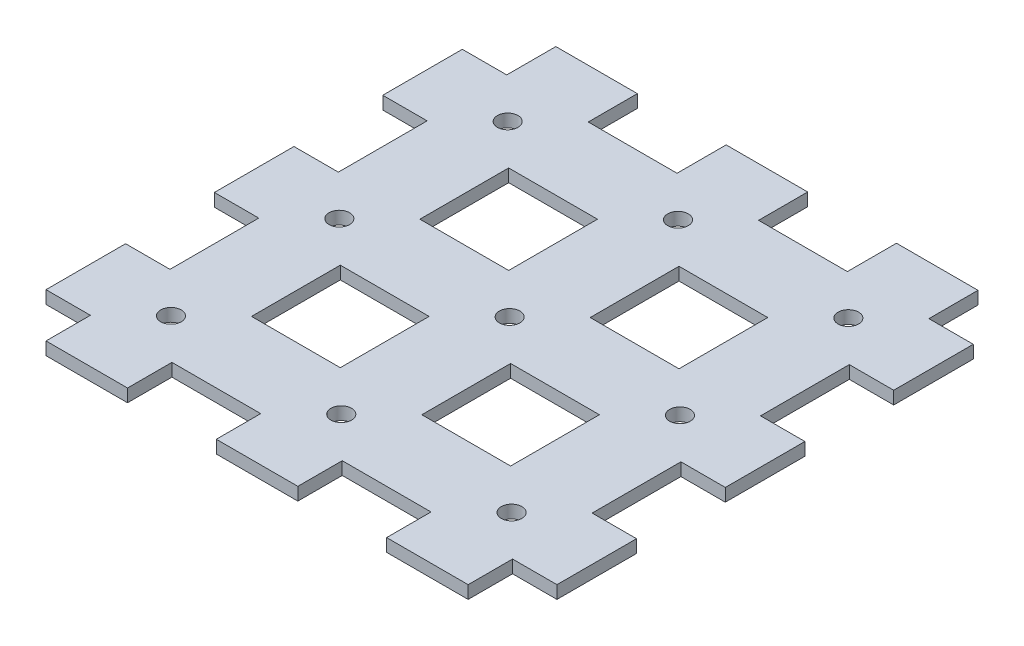
SolidWorks part; units mm, degrees
ref_plane "Front Plane" through (0, 0, 0) normal (0, 0, 1) x (1, 0, 0)
ref_plane "Top Plane" through (0, 0, 0) normal (0, 1, 0) x (1, 0, 0)
ref_plane "Right Plane" through (0, 0, 0) normal (1, 0, 0) x (0, 0, -1)
sketch "Sketch2" plane through (0, 0, 0) normal (0, 1, 0) x (1, 0, 0)
  line L1 (-63.3, 63.165) -> (63.3, 63.165)
  line L2 (-63.3, 63.165) -> (-63.3, -63.165)
  line L3 (-63.3, -63.165) -> (63.3, -63.165)
  line L4 (63.3, 63.165) -> (63.3, -63.165)
  line L5 (-63.3, 63.165) -> (63.3, -63.165) construction
  line L6 (-63.3, -63.165) -> (63.3, 63.165) construction
  point P0 (0, 0)
  dimension "D1" = 126.6
  dimension "D2" = 126.33
extrude "Boss-Extrude1" add sketch "Sketch2" along normal blind 3.175
sketch "Sketch3" plane through (0, 3.175, 0) normal (0, 1, 0) x (1, 0, 0)
  line L0 (63.3, -63.165) -> (63.3, 63.165) construction
  line L1 (52.3, -52.165) -> (74.3, -52.165)
  line L2 (52.3, -52.165) -> (52.3, -74.165)
  line L3 (52.3, -74.165) -> (74.3, -74.165)
  line L4 (74.3, -52.165) -> (74.3, -74.165)
  line L5 (52.3, -52.165) -> (74.3, -74.165) construction
  line L6 (52.3, -74.165) -> (74.3, -52.165) construction
  line L7 (-63.3, -63.165) -> (63.3, -63.165) construction
  line L8 (10.1, -52.165) -> (32.1, -52.165)
  line L9 (10.1, -52.165) -> (10.1, -74.165)
  line L10 (10.1, -74.165) -> (32.1, -74.165)
  line L11 (32.1, -52.165) -> (32.1, -74.165)
  line L12 (10.1, -52.165) -> (32.1, -74.165) construction
  line L13 (10.1, -74.165) -> (32.1, -52.165) construction
  line L14 (-32.1, -52.165) -> (-10.1, -52.165)
  line L15 (-32.1, -52.165) -> (-32.1, -74.165)
  line L16 (-32.1, -74.165) -> (-10.1, -74.165)
  line L17 (-10.1, -52.165) -> (-10.1, -74.165)
  line L18 (-32.1, -52.165) -> (-10.1, -74.165) construction
  line L19 (-32.1, -74.165) -> (-10.1, -52.165) construction
  line L20 (-74.3, -52.165) -> (-52.3, -52.165)
  line L21 (-74.3, -52.165) -> (-74.3, -74.165)
  line L22 (-74.3, -74.165) -> (-52.3, -74.165)
  line L23 (-52.3, -52.165) -> (-52.3, -74.165)
  line L24 (-74.3, -52.165) -> (-52.3, -74.165) construction
  line L25 (-74.3, -74.165) -> (-52.3, -52.165) construction
  line L26 (10.1, -10.445) -> (32.1, -10.445)
  line L27 (10.1, -10.445) -> (10.1, -32.445)
  line L28 (10.1, -32.445) -> (32.1, -32.445)
  line L29 (32.1, -10.445) -> (32.1, -32.445)
  line L30 (10.1, -10.445) -> (32.1, -32.445) construction
  line L31 (10.1, -32.445) -> (32.1, -10.445) construction
  line L32 (-32.1, -10.445) -> (-10.1, -10.445)
  line L33 (-32.1, -10.445) -> (-32.1, -32.445)
  line L34 (-32.1, -32.445) -> (-10.1, -32.445)
  line L35 (-10.1, -10.445) -> (-10.1, -32.445)
  line L36 (-32.1, -10.445) -> (-10.1, -32.445) construction
  line L37 (-32.1, -32.445) -> (-10.1, -10.445) construction
  line L38 (-74.3, -10.445) -> (-52.3, -10.445)
  line L39 (-74.3, -10.445) -> (-74.3, -32.445)
  line L40 (-74.3, -32.445) -> (-52.3, -32.445)
  line L41 (-52.3, -10.445) -> (-52.3, -32.445)
  line L42 (-74.3, -10.445) -> (-52.3, -32.445) construction
  line L43 (-74.3, -32.445) -> (-52.3, -10.445) construction
  line L44 (10.1, 31.275) -> (32.1, 31.275)
  line L45 (10.1, 31.275) -> (10.1, 9.275)
  line L46 (10.1, 9.275) -> (32.1, 9.275)
  line L47 (32.1, 31.275) -> (32.1, 9.275)
  line L48 (10.1, 31.275) -> (32.1, 9.275) construction
  line L49 (10.1, 9.275) -> (32.1, 31.275) construction
  line L50 (-32.1, 31.275) -> (-10.1, 31.275)
  line L51 (-32.1, 31.275) -> (-32.1, 9.275)
  line L52 (-32.1, 9.275) -> (-10.1, 9.275)
  line L53 (-10.1, 31.275) -> (-10.1, 9.275)
  line L54 (-32.1, 31.275) -> (-10.1, 9.275) construction
  line L55 (-32.1, 9.275) -> (-10.1, 31.275) construction
  line L56 (-74.3, 31.275) -> (-52.3, 31.275)
  line L57 (-74.3, 31.275) -> (-74.3, 9.275)
  line L58 (-74.3, 9.275) -> (-52.3, 9.275)
  line L59 (-52.3, 31.275) -> (-52.3, 9.275)
  line L60 (-74.3, 31.275) -> (-52.3, 9.275) construction
  line L61 (-74.3, 9.275) -> (-52.3, 31.275) construction
  line L62 (10.1, 72.995) -> (32.1, 72.995)
  line L63 (10.1, 72.995) -> (10.1, 50.995)
  line L64 (10.1, 50.995) -> (32.1, 50.995)
  line L65 (32.1, 72.995) -> (32.1, 50.995)
  line L66 (10.1, 72.995) -> (32.1, 50.995) construction
  line L67 (10.1, 50.995) -> (32.1, 72.995) construction
  line L68 (-32.1, 72.995) -> (-10.1, 72.995)
  line L69 (-32.1, 72.995) -> (-32.1, 50.995)
  line L70 (-32.1, 50.995) -> (-10.1, 50.995)
  line L71 (-10.1, 72.995) -> (-10.1, 50.995)
  line L72 (-32.1, 72.995) -> (-10.1, 50.995) construction
  line L73 (-32.1, 50.995) -> (-10.1, 72.995) construction
  line L74 (-74.3, 72.995) -> (-52.3, 72.995)
  line L75 (-74.3, 72.995) -> (-74.3, 50.995)
  line L76 (-74.3, 50.995) -> (-52.3, 50.995)
  line L77 (-52.3, 72.995) -> (-52.3, 50.995)
  line L78 (-74.3, 72.995) -> (-52.3, 50.995) construction
  line L79 (-74.3, 50.995) -> (-52.3, 72.995) construction
  line L80 (52.3, -10.445) -> (74.3, -10.445)
  line L81 (52.3, -10.445) -> (52.3, -32.445)
  line L82 (52.3, -32.445) -> (74.3, -32.445)
  line L83 (74.3, -10.445) -> (74.3, -32.445)
  line L84 (52.3, -10.445) -> (74.3, -32.445) construction
  line L85 (52.3, -32.445) -> (74.3, -10.445) construction
  line L86 (52.3, 31.275) -> (74.3, 31.275)
  line L87 (52.3, 31.275) -> (52.3, 9.275)
  line L88 (52.3, 9.275) -> (74.3, 9.275)
  line L89 (74.3, 31.275) -> (74.3, 9.275)
  line L90 (52.3, 31.275) -> (74.3, 9.275) construction
  line L91 (52.3, 9.275) -> (74.3, 31.275) construction
  line L92 (52.3, 72.995) -> (74.3, 72.995)
  line L93 (52.3, 72.995) -> (52.3, 50.995)
  line L94 (52.3, 50.995) -> (74.3, 50.995)
  line L95 (74.3, 72.995) -> (74.3, 50.995)
  line L96 (52.3, 72.995) -> (74.3, 50.995) construction
  line L97 (52.3, 50.995) -> (74.3, 72.995) construction
  point P0 (63.3, -63.165)
  point P12 (21.1, -63.165)
  point P17 (-21.1, -63.165)
  point P22 (-63.3, -63.165)
  point P27 (21.1, -21.445)
  point P32 (-21.1, -21.445)
  point P37 (-63.3, -21.445)
  point P42 (21.1, 20.275)
  point P47 (-21.1, 20.275)
  point P52 (-63.3, 20.275)
  point P57 (21.1, 61.995)
  point P62 (-21.1, 61.995)
  point P67 (-63.3, 61.995)
  point P72 (63.3, -21.445)
  point P77 (63.3, 20.275)
  point P82 (63.3, 61.995)
  dimension "D1" = 0
  dimension "D2" = 0
  dimension "D3" = 22
  dimension "D4" = 22
  dimension "D7" = 42.2
  dimension "D8" = 41.72
  dimension "D5" = 4
  dimension "D6" = 4
extrude "Cut-Extrude1" cut sketch "Sketch3" against normal through all
sketch "Sketch4" plane through (0, 3.175, 0) normal (0, 1, 0) x (1, 0, 0)
  line L0 (21.1, -32.445) -> (21.1, -52.165) construction
  line L1 (10.1, -32.445) -> (32.1, -32.445) construction
  line L2 (32.1, -52.165) -> (10.1, -52.165) construction
  line L3 (32.1, -57.665) -> (52.3, -57.665) construction
  line L4 (32.1, -63.165) -> (32.1, -52.165) construction
  line L5 (52.3, -52.165) -> (52.3, -63.165) construction
  circle A0 centre (42.2, -42.305) radius 2.55
  circle A1 centre (0, -42.305) radius 2.55
  circle A2 centre (-42.2, -42.305) radius 2.55
  circle A3 centre (0, -0.585) radius 2.55
  circle A4 centre (-42.2, -0.585) radius 2.55
  circle A5 centre (0, 41.135) radius 2.55
  circle A6 centre (-42.2, 41.135) radius 2.55
  circle A7 centre (42.2, -0.585) radius 2.55
  circle A8 centre (42.2, 41.135) radius 2.55
  point P14 (42.2, -57.665)
  point P15 (21.1, -42.305)
  dimension "D1" = 5.1
  dimension "D2" = 42.2
  dimension "D3" = 41.72
extrude "Cut-Extrude2" cut sketch "Sketch4" against normal through all
